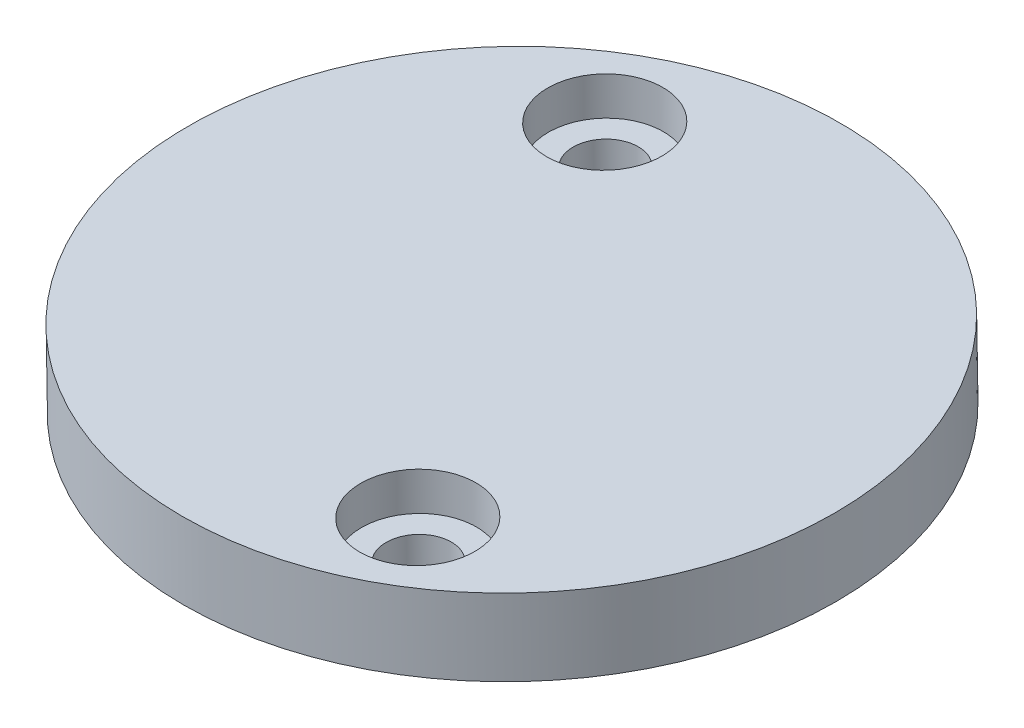
SolidWorks part; units mm, degrees
material "Custom Plastic"
ref_plane "Front Plane" through (0, 0, 0) normal (0, 0, 1) x (1, 0, 0)
ref_plane "Top Plane" through (0, 0, 0) normal (0, 1, 0) x (1, 0, 0)
ref_plane "Right Plane" through (0, 0, 0) normal (1, 0, 0) x (0, 0, -1)
sketch "Sketch1" plane through (0, 292.043, 5.0976) normal (0, 0.9998, 0.0175) x (1, 0, 0)
  circle A2 centre (109.8466, -203.1963) radius 17
  circle A12 centre (120.9109, -196.9617) radius 2.1
  circle A14 centre (98.7823, -209.4309) radius 2.1
  circle A15 centre (116.0812, -214.2606) radius 1.7
  circle A16 centre (103.612, -192.132) radius 1.7
extrude "Boss-Extrude1" add sketch "Sketch1" along normal blind 4
sketch "Sketch2" plane through (0, 296.0424, 5.1674) normal (0, 0.9998, 0.0175) x (1, 0, 0)
  circle A0 centre (98.7823, -209.4309) radius 2.1 construction
  circle A1 centre (120.9109, -196.9617) radius 2.1 construction
  circle A2 centre (98.7823, -209.4309) radius 2.1
  circle A3 centre (120.9109, -196.9617) radius 2.1
extrude "Boss-Extrude2" add sketch "Sketch2" against normal blind 6
sketch "Sketch3" plane through (0, 296.0424, 5.1674) normal (0, 0.9998, 0.0175) x (1, 0, 0)
  circle A0 centre (116.0812, -214.2606) radius 1.7 construction
  circle A1 centre (103.612, -192.132) radius 1.7 construction
  circle A2 centre (116.0812, -214.2606) radius 1.7
  circle A3 centre (103.612, -192.132) radius 1.7
  circle A4 centre (103.612, -192.132) radius 3
  circle A5 centre (116.0812, -214.2606) radius 3
extrude "Cut-Extrude1" cut sketch "Sketch3" against normal blind 2
